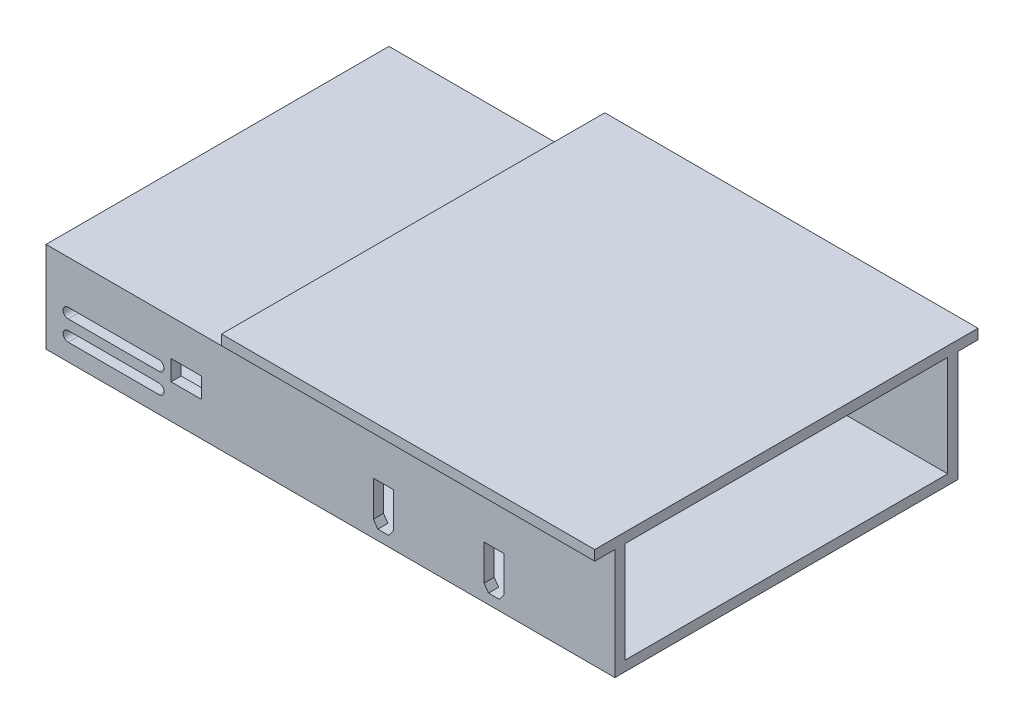
SolidWorks part; units mm, degrees
material "ABS"
ref_plane "Front Plane" through (0, 0, 0) normal (0, 0, 1) x (1, 0, 0)
ref_plane "Top Plane" through (0, 0, 0) normal (0, 1, 0) x (1, 0, 0)
ref_plane "Right Plane" through (0, 0, 0) normal (1, 0, 0) x (0, 0, -1)
sketch "Sketch1" plane through (0, 0, 0) normal (0, 1, 0) x (1, 0, 0)
  line L1 (0, 0) -> (282, 0)
  line L2 (0, 0) -> (0, 170)
  line L3 (0, 170) -> (282, 170)
  line L4 (282, 0) -> (282, 170)
  dimension "D1" = 170
  dimension "D2" = 282
extrude "Boss-Extrude1" add sketch "Sketch1" along normal blind 60
sketch "Sketch7" plane through (0, 0, 0) normal (0, -1, 0) x (1, 0, 0)
  line L0 (0, -170) -> (0, 0) construction
  line L3 (11, -37.5) -> (11, -132.5) construction
  line L4 (13.5, -37.5) -> (13.5, -132.5)
  line L5 (8.5, -37.5) -> (8.5, -132.5)
  line L6 (56, -37.5) -> (56, -132.5) construction
  line L7 (58.5, -37.5) -> (58.5, -132.5)
  line L8 (53.5, -37.5) -> (53.5, -132.5)
  line L9 (26, -37.5) -> (26, -132.5) construction
  line L10 (28.5, -37.5) -> (28.5, -132.5)
  line L11 (23.5, -37.5) -> (23.5, -132.5)
  line L12 (41, -37.5) -> (41, -132.5) construction
  line L13 (43.5, -37.5) -> (43.5, -132.5)
  line L14 (38.5, -37.5) -> (38.5, -132.5)
  line L15 (0, -85) -> (282, -85) construction
  line L16 (282, 0) -> (282, -170) construction
  arc A2 (13.5, -37.5) -> (8.5, -37.5) centre (11, -37.5) ccw
  arc A3 (8.5, -132.5) -> (13.5, -132.5) centre (11, -132.5) ccw
  arc A4 (58.5, -37.5) -> (53.5, -37.5) centre (56, -37.5) ccw
  arc A5 (53.5, -132.5) -> (58.5, -132.5) centre (56, -132.5) ccw
  arc A6 (28.5, -37.5) -> (23.5, -37.5) centre (26, -37.5) ccw
  arc A7 (23.5, -132.5) -> (28.5, -132.5) centre (26, -132.5) ccw
  arc A8 (43.5, -37.5) -> (38.5, -37.5) centre (41, -37.5) ccw
  arc A9 (38.5, -132.5) -> (43.5, -132.5) centre (41, -132.5) ccw
  point P9 (11, -85)
  point P16 (56, -85)
  point P23 (26, -85)
  point P30 (41, -85)
  point P35 (11, -35)
  point P36 (11, -135)
  point P42 (26, -35)
  point P43 (26, -135)
  point P44 (41, -35)
  point P45 (41, -135)
  point P46 (56, -35)
  point P47 (56, -135)
  dimension "D1" = 8.5
  dimension "D6" = 100
  dimension "D7" = 100
  dimension "D9" = 100
  dimension "D2" = 5
  dimension "D3" = 5
  dimension "D4" = 5
  dimension "D5" = 5
  dimension "D8" = 100
  dimension "D10" = 15
  dimension "D11" = 15
  dimension "D12" = 15
extrude "Cut-Extrude4" cut sketch "Sketch7" against normal blind 5
sketch "Sketch8" plane through (282, 0, 0) normal (1, 0, 0) x (0, 0, -1)
  line L0 (0, 60) -> (0, 0) construction
  line L1 (5, 55) -> (165, 55)
  line L2 (5, 55) -> (5, 5)
  line L3 (5, 5) -> (165, 5)
  line L4 (165, 55) -> (165, 5)
  line L5 (170, 60) -> (170, 0) construction
  line L6 (0, 0) -> (170, 0) construction
  line L7 (0, 60) -> (170, 60) construction
  dimension "D1" = 5
  dimension "D2" = 5
  dimension "D3" = 5
  dimension "D4" = 5
extrude "Cut-Extrude5" cut sketch "Sketch8" against normal blind 279
sketch "Sketch9" plane through (0, 0, 0) normal (0, 0, 1) x (1, 0, 0)
  line L0 (217.15, 25.8) -> (227.05, 25.8)
  line L1 (162.25, 25.8) -> (172.15, 25.8)
  line L2 (162.25, 25.8) -> (162.25, 8.15)
  line L3 (164.5, 5) -> (169.9, 5)
  line L4 (172.15, 25.8) -> (172.15, 8.15)
  line L5 (217.15, 25.8) -> (217.15, 8.15)
  line L6 (219.4, 5) -> (224.8, 5)
  line L7 (227.05, 25.8) -> (227.05, 8.15)
  line L8 (282, 60) -> (282, 0) construction
  line L9 (0, 0) -> (282, 0) construction
  line L10 (162.25, 8.15) -> (164.5, 5)
  line L11 (169.9, 5) -> (172.15, 8.15)
  line L12 (217.15, 8.15) -> (219.4, 5)
  line L13 (227.05, 8.15) -> (224.8, 5)
  dimension "D1" = 9.9
  dimension "D2" = 3.15
  dimension "D3" = 54.95
  dimension "D4" = 45
  dimension "D5" = 9.9
  dimension "D6" = 20.8
  dimension "D7" = 5
  dimension "D8" = 2.25
  dimension "D9" = 20.8
  dimension "D10" = 2.25
  dimension "D11" = 3.15
  dimension "D12" = 3.15
  dimension "D13" = 3.15
  dimension "D14" = 2.25
  dimension "D15" = 2.25
  dimension "D16" = 25.8
extrude "Cut-Extrude6" cut sketch "Sketch9" against normal blind 5
sketch "Sketch10" plane through (0, 0, 0) normal (-1, 0, 0) x (0, 0, 1)
  line L0 (-170, 20) -> (0, 20) construction
  line L1 (-170, 60) -> (-170, 0) construction
  line L2 (0, 60) -> (0, 0) construction
  line L3 (-170, 0) -> (0, 0) construction
  circle A0 centre (-129.2022, 20) radius 5
  circle A1 centre (-114.2022, 20) radius 5
  circle A2 centre (-99.2022, 20) radius 5
  circle A3 centre (-43.3901, 20) radius 5
  circle A4 centre (-58.3901, 20) radius 5
  circle A5 centre (-73.3901, 20) radius 5
  dimension "D1" = 15
  dimension "D3" = 10
  dimension "D4" = 10
  dimension "D5" = 10
  dimension "D6" = 10
  dimension "D7" = 10
  dimension "D8" = 10
  dimension "D2" = 15
  dimension "D9" = 15
  dimension "D10" = 15
  dimension "D11" = 20
extrude "Cut-Extrude7" cut sketch "Sketch10" against normal blind 5
sketch "Sketch11" plane through (0, 0, 0) normal (0, 0, 1) x (1, 0, 0)
  line L0 (11, 11) -> (56, 11) construction
  line L1 (11, 13.5) -> (56, 13.5)
  line L2 (11, 8.5) -> (56, 8.5)
  line L3 (11, 21) -> (56, 21) construction
  line L4 (11, 23.5) -> (56, 23.5)
  line L5 (11, 18.5) -> (56, 18.5)
  line L9 (0, 60) -> (0, 0) construction
  line L10 (0, 0) -> (282, 0) construction
  arc A0 (11, 13.5) -> (11, 8.5) centre (11, 11) ccw
  arc A1 (56, 8.5) -> (56, 13.5) centre (56, 11) ccw
  arc A2 (11, 23.5) -> (11, 18.5) centre (11, 21) ccw
  arc A3 (56, 18.5) -> (56, 23.5) centre (56, 21) ccw
  point P2 (33.5, 11)
  point P9 (33.5, 21)
  point P21 (8.5, 11)
  point P24 (33.5, 8.5)
  point P27 (58.5, 11)
  point P28 (58.5, 21)
  point P29 (8.5, 21)
  dimension "D1" = 8.5
  dimension "D2" = 8.5
  dimension "D3" = 5
  dimension "D4" = 5
  dimension "D6" = 50
  dimension "D7" = 50
  dimension "D9" = 5
sketch "Sketch12" plane through (0, 0, -170) normal (0, 0, -1) x (-1, 0, 0)
  line L0 (-56, 11) -> (-11, 11) construction
  line L1 (-56, 13.5) -> (-11, 13.5)
  line L2 (-56, 8.5) -> (-11, 8.5)
  line L3 (-56, 21) -> (-11, 21) construction
  line L4 (-56, 23.5) -> (-11, 23.5)
  line L5 (-56, 18.5) -> (-11, 18.5)
  line L9 (-282, 0) -> (0, 0) construction
  line L10 (0, 60) -> (0, 0) construction
  arc A0 (-56, 13.5) -> (-56, 8.5) centre (-56, 11) ccw
  arc A1 (-11, 8.5) -> (-11, 13.5) centre (-11, 11) ccw
  arc A2 (-56, 23.5) -> (-56, 18.5) centre (-56, 21) ccw
  arc A3 (-11, 18.5) -> (-11, 23.5) centre (-11, 21) ccw
  point P2 (-33.5, 11)
  point P12 (-33.5, 21)
  point P26 (-8.5, 11)
  point P27 (-58.5, 11)
  point P28 (-8.5, 21)
  point P29 (-58.5, 21)
  dimension "D1" = 8.5
  dimension "D2" = 5
  dimension "D3" = 5
  dimension "D5" = 50
  dimension "D6" = 50
  dimension "D8" = 8.5
  dimension "D9" = 5
extrude "Cut-Extrude8" cut sketch "Sketch11" against normal blind 5
extrude "Cut-Extrude9" cut sketch "Sketch12" against normal blind 5
sketch "Sketch14" plane through (0, 0, 0) normal (0, 0, 1) x (1, 0, 0)
  line L0 (282, 60) -> (282, 0) construction
  line L1 (282, 60) -> (97, 60)
  line L2 (282, 60) -> (282, 55)
  line L3 (282, 55) -> (97, 55)
  line L4 (97, 60) -> (97, 55)
  line L5 (0, 60) -> (282, 60) construction
  dimension "D1" = 5
  dimension "D2" = 185
extrude "Boss-Extrude2" add sketch "Sketch14" along normal blind 10
sketch "Sketch15" plane through (0, 0, -170) normal (0, 0, -1) x (-1, 0, 0)
  line L1 (-282, 60) -> (-97, 60)
  line L2 (-282, 60) -> (-282, 55)
  line L3 (-282, 55) -> (-97, 55)
  line L4 (-97, 60) -> (-97, 55)
  dimension "D1" = 5
  dimension "D2" = 185
extrude "Boss-Extrude3" add sketch "Sketch15" along normal blind 10
sketch "Sketch16" plane through (0, 0, 0) normal (0, 0, 1) x (1, 0, 0)
  line L0 (97, 60) -> (97, 55) construction
  line L1 (0, 60) -> (97, 60)
  line L2 (0, 60) -> (0, 45)
  line L3 (0, 45) -> (97, 45)
  line L4 (97, 60) -> (97, 45)
  dimension "D2" = 15
extrude "Cut-Extrude10" cut sketch "Sketch16" against normal blind 170
sketch "Sketch17" plane through (0, 0, -165) normal (0, 0, 1) x (1, 0, 0)
  line L1 (3, 45) -> (97, 45)
  line L2 (3, 45) -> (3, 40)
  line L5 (97, 55) -> (282, 55) construction
  line L7 (97, 45) -> (97, 55)
  line L8 (97, 55) -> (102, 55)
  line L9 (102, 40) -> (102, 55)
  line L11 (102, 40) -> (3, 40)
  line L12 (97, 55) -> (97, 45) construction
  dimension "D1" = 5
  dimension "D2" = 5
extrude "Boss-Extrude4" add sketch "Sketch17" along normal blind 160
sketch "Sketch18" plane through (0, 0, 0) normal (0, 0, 1) x (1, 0, 0)
  line L1 (62, 27) -> (77, 27)
  line L2 (62, 27) -> (62, 17)
  line L3 (62, 17) -> (77, 17)
  line L4 (77, 27) -> (77, 17)
  line L5 (97, 45) -> (97, 55) construction
  line L8 (0, 45) -> (97, 45) construction
  dimension "D1" = 15
  dimension "D2" = 10
  dimension "D3" = 18
  dimension "D4" = 20
extrude "Cut-Extrude11" cut sketch "Sketch18" against normal through all
